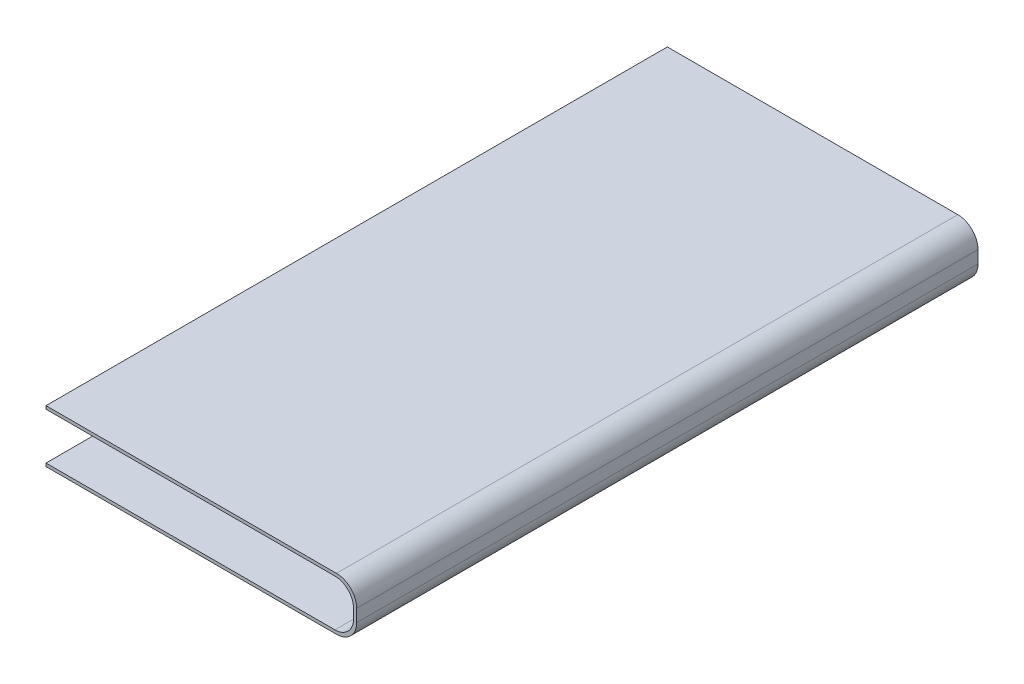
SolidWorks part; units mm, degrees
ref_plane "Спереди" through (0, 0, 0) normal (0, 0, 1) x (1, 0, 0)
ref_plane "Сверху" through (0, 0, 0) normal (0, 1, 0) x (1, 0, 0)
ref_plane "Справа" through (0, 0, 0) normal (1, 0, 0) x (0, 0, -1)
sketch "Эскиз1" plane through (0, 0, 0) normal (0, 0, 1) x (1, 0, 0)
  line L0 (14.4, -1.65) -> (23.75, -1.65)
  line L1 (-27.15, -1.65) -> (27.15, -1.65) construction
  line L2 (24.4, -2.3) -> (24.4, -2.7)
  line L3 (23.75, -3.35) -> (14.4, -3.35)
  line L4 (14.4, -1.75) -> (23.7, -1.75)
  line L5 (24.3, -2.35) -> (24.3, -2.65)
  line L6 (23.7, -3.25) -> (14.4, -3.25)
  line L7 (14.4, -1.65) -> (14.4, -1.75)
  line L8 (14.4, -3.25) -> (14.4, -3.35)
  line L9 (23.9, -4.25) -> (23.9, -1.65) construction
  line L10 (24.4, -1.65) -> (24.4, -3.35) construction
  line L11 (24.4, -3.35) -> (14.4, -3.35) construction
  line L12 (14.4, -1.65) -> (24.4, -1.65) construction
  line L13 (24.3, -1.75) -> (24.3, -3.25) construction
  line L14 (24.3, -3.25) -> (14.4, -3.25) construction
  line L15 (14.4, -1.75) -> (24.3, -1.75) construction
  arc A0 (24.4, -2.7) -> (23.75, -3.35) centre (23.75, -2.7) cw
  arc A1 (23.75, -1.65) -> (24.4, -2.3) centre (23.75, -2.3) cw
  arc A2 (24.3, -2.65) -> (23.7, -3.25) centre (23.7, -2.65) cw
  arc A3 (23.7, -1.75) -> (24.3, -2.35) centre (23.7, -2.35) cw
  point P15 (24.4, -3.35)
  dimension "D5" = 0.65
  dimension "D6" = 0.6
  dimension "D2" = 0.5
  dimension "D3" = 1.7
  dimension "D4" = 10
  dimension "D1" = 0.1
extrude "Бобышка-Вытянуть1" add sketch "Эскиз1" along normal mid plane 20
